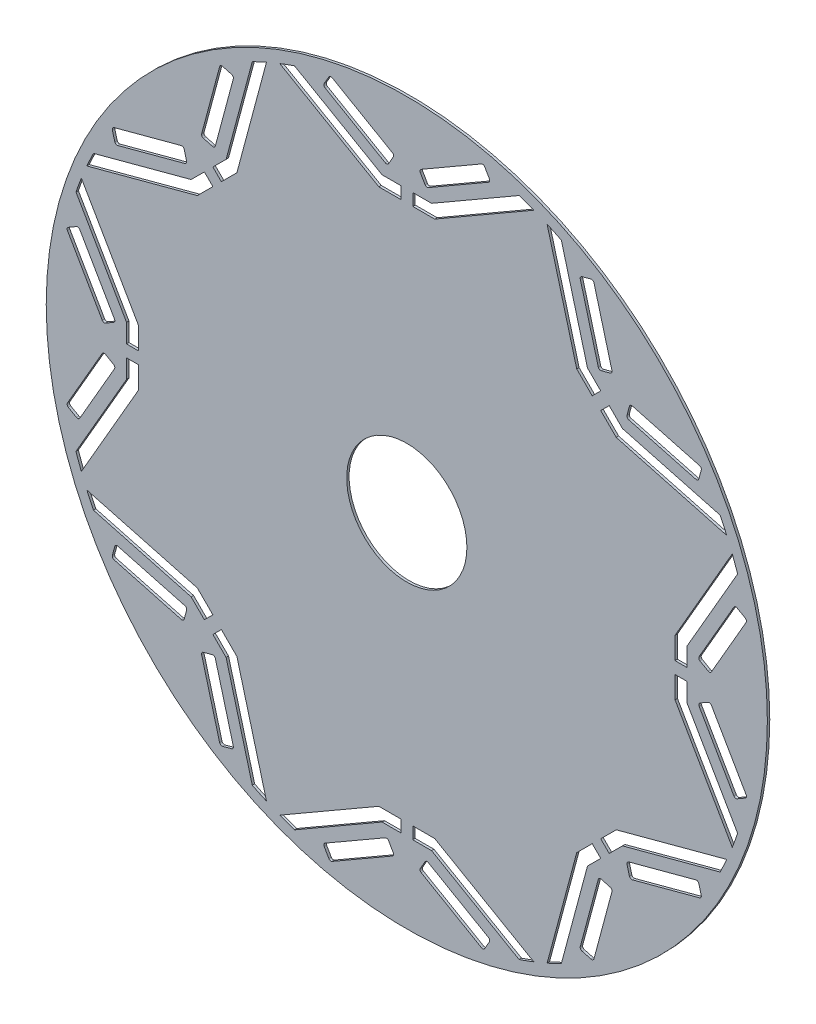
SolidWorks part; units mm, degrees
material "M19 Silicon Steel (29 Gauge)"
ref_plane "Front Plane" through (0, 0, 0) normal (0, 0, 1) x (1, 0, 0)
ref_plane "Top Plane" through (0, 0, 0) normal (0, 1, 0) x (1, 0, 0)
ref_plane "Right Plane" through (0, 0, 0) normal (1, 0, 0) x (0, 0, -1)
sketch "Rotor sketch" plane through (0, 0, 0) normal (0, 0, 1) x (1, 0, 0)
  line L0 (0, 0) -> (0, 45) construction
  line L1 (2.6839, 36.4771) -> (10.2011, 40.8171)
  line L2 (2.2741, 36.5869) -> (1.6891, 37.6002)
  line L3 (10.3109, 41.2269) -> (9.7259, 42.2402)
  line L4 (1.7989, 38.01) -> (9.3161, 42.35)
  line L5 (2.4241, 36.3271) -> (9.5759, 42.5) construction
  line L6 (10.4609, 40.9671) -> (1.5391, 37.86) construction
  line L7 (-10.4609, 40.9671) -> (-1.5391, 37.86) construction
  line L8 (-2.4241, 36.3271) -> (-9.5759, 42.5) construction
  line L9 (-1.7989, 38.01) -> (-9.3161, 42.35)
  line L10 (-10.3109, 41.2269) -> (-9.7259, 42.2402)
  line L11 (-2.2741, 36.5869) -> (-1.6891, 37.6002)
  line L12 (-2.6839, 36.4771) -> (-10.2011, 40.8171)
  line L13 (25.6051, 28.1492) -> (23.3585, 36.5334)
  line L14 (24.2628, 27.4789) -> (25.3929, 27.7818)
  line L15 (23.8954, 27.6911) -> (21.6488, 36.0753)
  line L16 (21.861, 36.4427) -> (22.9911, 36.7455)
  line L17 (27.4789, 24.2628) -> (27.7818, 25.3929)
  line L18 (28.1492, 25.6051) -> (36.5334, 23.3585)
  line L19 (36.4427, 21.861) -> (36.7455, 22.9911)
  line L20 (27.6911, 23.8954) -> (36.0753, 21.6488)
  line L21 (38.01, 1.7989) -> (42.35, 9.3161)
  line L22 (36.5869, 2.2741) -> (37.6002, 1.6891)
  line L23 (36.4771, 2.6839) -> (40.8171, 10.2011)
  line L24 (41.2269, 10.3109) -> (42.2402, 9.7259)
  line L25 (36.5869, -2.2741) -> (37.6002, -1.6891)
  line L26 (38.01, -1.7989) -> (42.35, -9.3161)
  line L27 (41.2269, -10.3109) -> (42.2402, -9.7259)
  line L28 (36.4771, -2.6839) -> (40.8171, -10.2011)
  line L29 (28.1492, -25.6051) -> (36.5334, -23.3585)
  line L30 (27.4789, -24.2628) -> (27.7818, -25.3929)
  line L31 (27.6911, -23.8954) -> (36.0753, -21.6488)
  line L32 (36.4427, -21.861) -> (36.7455, -22.9911)
  line L33 (24.2628, -27.4789) -> (25.3929, -27.7818)
  line L34 (25.6051, -28.1492) -> (23.3585, -36.5334)
  line L35 (21.861, -36.4427) -> (22.9911, -36.7455)
  line L36 (23.8954, -27.6911) -> (21.6488, -36.0753)
  line L37 (1.7989, -38.01) -> (9.3161, -42.35)
  line L38 (2.2741, -36.5869) -> (1.6891, -37.6002)
  line L39 (2.6839, -36.4771) -> (10.2011, -40.8171)
  line L40 (10.3109, -41.2269) -> (9.7259, -42.2402)
  line L41 (-2.2741, -36.5869) -> (-1.6891, -37.6002)
  line L42 (-1.7989, -38.01) -> (-9.3161, -42.35)
  line L43 (-10.3109, -41.2269) -> (-9.7259, -42.2402)
  line L44 (-2.6839, -36.4771) -> (-10.2011, -40.8171)
  line L45 (-25.6051, -28.1492) -> (-23.3585, -36.5334)
  line L46 (-24.2628, -27.4789) -> (-25.3929, -27.7818)
  line L47 (-23.8954, -27.6911) -> (-21.6488, -36.0753)
  line L48 (-21.861, -36.4427) -> (-22.9911, -36.7455)
  line L49 (-27.4789, -24.2628) -> (-27.7818, -25.3929)
  line L50 (-28.1492, -25.6051) -> (-36.5334, -23.3585)
  line L51 (-36.4427, -21.861) -> (-36.7455, -22.9911)
  line L52 (-27.6911, -23.8954) -> (-36.0753, -21.6488)
  line L53 (-38.01, -1.7989) -> (-42.35, -9.3161)
  line L54 (-36.5869, -2.2741) -> (-37.6002, -1.6891)
  line L55 (-36.4771, -2.6839) -> (-40.8171, -10.2011)
  line L56 (-41.2269, -10.3109) -> (-42.2402, -9.7259)
  line L57 (-36.5869, 2.2741) -> (-37.6002, 1.6891)
  line L58 (-38.01, 1.7989) -> (-42.35, 9.3161)
  line L59 (-41.2269, 10.3109) -> (-42.2402, 9.7259)
  line L60 (-36.4771, 2.6839) -> (-40.8171, 10.2011)
  line L61 (-28.1492, 25.6051) -> (-36.5334, 23.3585)
  line L62 (-27.4789, 24.2628) -> (-27.7818, 25.3929)
  line L63 (-27.6911, 23.8954) -> (-36.0753, 21.6488)
  line L64 (-36.4427, 21.861) -> (-36.7455, 22.9911)
  line L65 (-24.2628, 27.4789) -> (-25.3929, 27.7818)
  line L66 (-25.6051, 28.1492) -> (-23.3585, 36.5334)
  line L67 (-21.861, 36.4427) -> (-22.9911, 36.7455)
  line L68 (-23.8954, 27.6911) -> (-21.6488, 36.0753)
  line L69 (0, 0) -> (-9.8912, 43.8995) construction
  circle A0 centre (0, 0) radius 45
  circle A1 centre (0, 0) radius 7.5
  arc A2 (-21.861, 36.4427) -> (-21.6488, 36.0753) centre (-21.9386, 36.153) cw
  arc A3 (-23.3585, 36.5334) -> (-22.9911, 36.7455) centre (-23.0688, 36.4558) cw
  arc A4 (-24.2628, 27.4789) -> (-23.8954, 27.6911) centre (-24.1852, 27.7687) ccw
  arc A5 (-25.3929, 27.7818) -> (-25.6051, 28.1492) centre (-25.3153, 28.0715) cw
  arc A6 (-27.4789, 24.2628) -> (-27.6911, 23.8954) centre (-27.7687, 24.1852) cw
  arc A7 (-28.1492, 25.6051) -> (-27.7818, 25.3929) centre (-28.0715, 25.3153) cw
  arc A8 (-36.5334, 23.3585) -> (-36.7455, 22.9911) centre (-36.4558, 23.0688) ccw
  arc A9 (-36.0753, 21.6488) -> (-36.4427, 21.861) centre (-36.153, 21.9386) cw
  arc A10 (-36.5869, 2.2741) -> (-36.4771, 2.6839) centre (-36.7369, 2.5339) ccw
  arc A11 (-37.6002, 1.6891) -> (-38.01, 1.7989) centre (-37.7502, 1.9489) cw
  arc A12 (-41.2269, 10.3109) -> (-40.8171, 10.2011) centre (-41.0769, 10.0511) cw
  arc A13 (-42.35, 9.3161) -> (-42.2402, 9.7259) centre (-42.0902, 9.4661) cw
  arc A14 (-36.5869, -2.2741) -> (-36.4771, -2.6839) centre (-36.7369, -2.5339) cw
  arc A15 (-38.01, -1.7989) -> (-37.6002, -1.6891) centre (-37.7502, -1.9489) cw
  arc A16 (-42.35, -9.3161) -> (-42.2402, -9.7259) centre (-42.0902, -9.4661) ccw
  arc A17 (-40.8171, -10.2011) -> (-41.2269, -10.3109) centre (-41.0769, -10.0511) cw
  arc A18 (-36.5334, -23.3585) -> (-36.7455, -22.9911) centre (-36.4558, -23.0688) cw
  arc A19 (-36.4427, -21.861) -> (-36.0753, -21.6488) centre (-36.153, -21.9386) cw
  arc A20 (-27.4789, -24.2628) -> (-27.6911, -23.8954) centre (-27.7687, -24.1852) ccw
  arc A21 (-27.7818, -25.3929) -> (-28.1492, -25.6051) centre (-28.0715, -25.3153) cw
  arc A22 (-24.2628, -27.4789) -> (-23.8954, -27.6911) centre (-24.1852, -27.7687) cw
  arc A23 (-25.6051, -28.1492) -> (-25.3929, -27.7818) centre (-25.3153, -28.0715) cw
  arc A24 (-23.3585, -36.5334) -> (-22.9911, -36.7455) centre (-23.0688, -36.4558) ccw
  arc A25 (-21.6488, -36.0753) -> (-21.861, -36.4427) centre (-21.9386, -36.153) cw
  arc A26 (-10.3109, -41.2269) -> (-10.2011, -40.8171) centre (-10.0511, -41.0769) cw
  arc A27 (-9.3161, -42.35) -> (-9.7259, -42.2402) centre (-9.4661, -42.0902) cw
  arc A28 (-1.6891, -37.6002) -> (-1.7989, -38.01) centre (-1.9489, -37.7502) cw
  arc A29 (-2.2741, -36.5869) -> (-2.6839, -36.4771) centre (-2.5339, -36.7369) ccw
  arc A30 (10.2011, -40.8171) -> (10.3109, -41.2269) centre (10.0511, -41.0769) cw
  arc A31 (9.3161, -42.35) -> (9.7259, -42.2402) centre (9.4661, -42.0902) ccw
  arc A32 (1.7989, -38.01) -> (1.6891, -37.6002) centre (1.9489, -37.7502) cw
  arc A33 (2.2741, -36.5869) -> (2.6839, -36.4771) centre (2.5339, -36.7369) cw
  arc A34 (23.3585, -36.5334) -> (22.9911, -36.7455) centre (23.0688, -36.4558) cw
  arc A35 (21.861, -36.4427) -> (21.6488, -36.0753) centre (21.9386, -36.153) cw
  arc A36 (24.2628, -27.4789) -> (23.8954, -27.6911) centre (24.1852, -27.7687) ccw
  arc A37 (25.3929, -27.7818) -> (25.6051, -28.1492) centre (25.3153, -28.0715) cw
  arc A38 (28.1492, -25.6051) -> (27.7818, -25.3929) centre (28.0715, -25.3153) cw
  arc A39 (27.4789, -24.2628) -> (27.6911, -23.8954) centre (27.7687, -24.1852) cw
  arc A40 (36.5334, -23.3585) -> (36.7455, -22.9911) centre (36.4558, -23.0688) ccw
  arc A41 (36.0753, -21.6488) -> (36.4427, -21.861) centre (36.153, -21.9386) cw
  arc A42 (41.2269, -10.3109) -> (40.8171, -10.2011) centre (41.0769, -10.0511) cw
  arc A43 (42.35, -9.3161) -> (42.2402, -9.7259) centre (42.0902, -9.4661) cw
  arc A44 (37.6002, -1.6891) -> (38.01, -1.7989) centre (37.7502, -1.9489) cw
  arc A45 (36.5869, -2.2741) -> (36.4771, -2.6839) centre (36.7369, -2.5339) ccw
  arc A46 (38.01, 1.7989) -> (37.6002, 1.6891) centre (37.7502, 1.9489) cw
  arc A47 (36.5869, 2.2741) -> (36.4771, 2.6839) centre (36.7369, 2.5339) cw
  arc A48 (40.8171, 10.2011) -> (41.2269, 10.3109) centre (41.0769, 10.0511) cw
  arc A49 (42.35, 9.3161) -> (42.2402, 9.7259) centre (42.0902, 9.4661) ccw
  arc A50 (36.4427, 21.861) -> (36.0753, 21.6488) centre (36.153, 21.9386) cw
  arc A51 (36.5334, 23.3585) -> (36.7455, 22.9911) centre (36.4558, 23.0688) cw
  arc A52 (27.4789, 24.2628) -> (27.6911, 23.8954) centre (27.7687, 24.1852) ccw
  arc A53 (27.7818, 25.3929) -> (28.1492, 25.6051) centre (28.0715, 25.3153) cw
  arc A54 (24.2628, 27.4789) -> (23.8954, 27.6911) centre (24.1852, 27.7687) cw
  arc A55 (25.6051, 28.1492) -> (25.3929, 27.7818) centre (25.3153, 28.0715) cw
  arc A56 (23.3585, 36.5334) -> (22.9911, 36.7455) centre (23.0688, 36.4558) ccw
  arc A57 (21.6488, 36.0753) -> (21.861, 36.4427) centre (21.9386, 36.153) cw
  arc A58 (10.2011, 40.8171) -> (10.3109, 41.2269) centre (10.0511, 41.0769) ccw
  arc A59 (9.7259, 42.2402) -> (9.3161, 42.35) centre (9.4661, 42.0902) ccw
  arc A60 (1.6891, 37.6002) -> (1.7989, 38.01) centre (1.9489, 37.7502) cw
  arc A61 (2.2741, 36.5869) -> (2.6839, 36.4771) centre (2.5339, 36.7369) ccw
  arc A62 (-10.2011, 40.8171) -> (-10.3109, 41.2269) centre (-10.0511, 41.0769) cw
  arc A63 (-2.6839, 36.4771) -> (-2.2741, 36.5869) centre (-2.5339, 36.7369) ccw
  arc A64 (-1.6891, 37.6002) -> (-1.7989, 38.01) centre (-1.9489, 37.7502) ccw
  arc A65 (-9.7259, 42.2402) -> (-9.3161, 42.35) centre (-9.4661, 42.0902) cw
  point P6 (6, 39.4136)
  point P16 (-6, 39.4136)
  point P74 (0, 0)
  dimension "D6" = 90
  dimension "D7" = 15
  dimension "D10" = 0.3
  dimension "D1" = 9.28
  dimension "D2" = 1.77
  dimension "D3" = 60
  dimension "D4" = 6
  dimension "D5" = 2.5
  dimension "D9" = 1.4346
  dimension "D8" = 8
extrude "Boss-Extrude1" add sketch "Rotor sketch" along normal mid plane 0.3
sketch "Saliency grooves" plane through (0, 0, 0.15) normal (0, 0, 1) x (1, 0, 0)
  line L0 (-12.8371, 38.875) -> (-3.4878, 33.4771)
  line L3 (-14.0139, 41.2864) -> (-3.0859, 34.9771)
  line L4 (0.75, 34.9771) -> (3.0859, 34.9771)
  line L5 (-3.4878, 33.4771) -> (-14.0139, 41.2864) construction
  line L6 (0, 0) -> (0, 45) construction
  line L7 (3.4878, 33.4771) -> (14.0139, 41.2864) construction
  line L8 (-0.75, 33.4771) -> (-3.4878, 33.4771)
  line L9 (14.0139, 41.2864) -> (3.0859, 34.9771)
  line L12 (12.8371, 38.875) -> (3.4878, 33.4771)
  line L13 (-3.0859, 34.9771) -> (-0.75, 34.9771)
  line L14 (3.4878, 33.4771) -> (0.75, 33.4771)
  line L15 (0, 43.6) -> (0, 45) construction
  line L16 (-10.2011, 40.8171) -> (-2.6839, 36.4771) construction
  line L17 (-10.2011, 40.8171) -> (-2.6839, 36.4771) construction
  line L18 (-0.75, 33.4771) -> (0.75, 34.9771) construction
  line L20 (-0.75, 33.4771) -> (-0.75, 34.9771)
  line L22 (0.75, 33.4771) -> (0.75, 34.9771)
  line L23 (-12.8371, 38.875) -> (-15.8526, 40.616)
  line L24 (12.8371, 38.875) -> (15.8526, 40.616)
  line L25 (19.2846, 39.1033) -> (22.5505, 26.9146)
  line L26 (18.4115, 36.566) -> (21.2057, 26.1382)
  line L27 (18.4115, 36.566) -> (17.5103, 39.9293)
  line L28 (23.1416, 24.2022) -> (21.2057, 26.1382)
  line L29 (22.5505, 26.9146) -> (24.2022, 25.2629)
  line L30 (23.1416, 24.2022) -> (24.2022, 25.2629)
  line L31 (25.2629, 24.2022) -> (26.9146, 22.5505)
  line L32 (24.2022, 23.1416) -> (25.2629, 24.2022)
  line L33 (26.1382, 21.2057) -> (24.2022, 23.1416)
  line L34 (36.566, 18.4115) -> (26.1382, 21.2057)
  line L35 (39.1033, 19.2846) -> (26.9146, 22.5505)
  line L36 (36.566, 18.4115) -> (39.9293, 17.5103)
  line L37 (41.2864, 14.0139) -> (34.9771, 3.0859)
  line L38 (38.875, 12.8371) -> (33.4771, 3.4878)
  line L39 (38.875, 12.8371) -> (40.616, 15.8526)
  line L40 (33.4771, 0.75) -> (33.4771, 3.4878)
  line L41 (34.9771, 3.0859) -> (34.9771, 0.75)
  line L42 (33.4771, 0.75) -> (34.9771, 0.75)
  line L43 (34.9771, -0.75) -> (34.9771, -3.0859)
  line L44 (33.4771, -0.75) -> (34.9771, -0.75)
  line L45 (33.4771, -3.4878) -> (33.4771, -0.75)
  line L46 (38.875, -12.8371) -> (33.4771, -3.4878)
  line L47 (41.2864, -14.0139) -> (34.9771, -3.0859)
  line L48 (38.875, -12.8371) -> (40.616, -15.8526)
  line L49 (39.1033, -19.2846) -> (26.9146, -22.5505)
  line L50 (36.566, -18.4115) -> (26.1382, -21.2057)
  line L51 (36.566, -18.4115) -> (39.9293, -17.5103)
  line L52 (24.2022, -23.1416) -> (26.1382, -21.2057)
  line L53 (26.9146, -22.5505) -> (25.2629, -24.2022)
  line L54 (24.2022, -23.1416) -> (25.2629, -24.2022)
  line L55 (24.2022, -25.2629) -> (22.5505, -26.9146)
  line L56 (23.1416, -24.2022) -> (24.2022, -25.2629)
  line L57 (21.2057, -26.1382) -> (23.1416, -24.2022)
  line L58 (18.4115, -36.566) -> (21.2057, -26.1382)
  line L59 (19.2846, -39.1033) -> (22.5505, -26.9146)
  line L60 (18.4115, -36.566) -> (17.5103, -39.9293)
  line L61 (14.0139, -41.2864) -> (3.0859, -34.9771)
  line L62 (12.8371, -38.875) -> (3.4878, -33.4771)
  line L63 (12.8371, -38.875) -> (15.8526, -40.616)
  line L64 (0.75, -33.4771) -> (3.4878, -33.4771)
  line L65 (3.0859, -34.9771) -> (0.75, -34.9771)
  line L66 (0.75, -33.4771) -> (0.75, -34.9771)
  line L67 (-0.75, -34.9771) -> (-3.0859, -34.9771)
  line L68 (-0.75, -33.4771) -> (-0.75, -34.9771)
  line L69 (-3.4878, -33.4771) -> (-0.75, -33.4771)
  line L70 (-12.8371, -38.875) -> (-3.4878, -33.4771)
  line L71 (-14.0139, -41.2864) -> (-3.0859, -34.9771)
  line L72 (-12.8371, -38.875) -> (-15.8526, -40.616)
  line L73 (-19.2846, -39.1033) -> (-22.5505, -26.9146)
  line L74 (-18.4115, -36.566) -> (-21.2057, -26.1382)
  line L75 (-18.4115, -36.566) -> (-17.5103, -39.9293)
  line L76 (-23.1416, -24.2022) -> (-21.2057, -26.1382)
  line L77 (-22.5505, -26.9146) -> (-24.2022, -25.2629)
  line L78 (-23.1416, -24.2022) -> (-24.2022, -25.2629)
  line L79 (-25.2629, -24.2022) -> (-26.9146, -22.5505)
  line L80 (-24.2022, -23.1416) -> (-25.2629, -24.2022)
  line L81 (-26.1382, -21.2057) -> (-24.2022, -23.1416)
  line L82 (-36.566, -18.4115) -> (-26.1382, -21.2057)
  line L83 (-39.1033, -19.2846) -> (-26.9146, -22.5505)
  line L84 (-36.566, -18.4115) -> (-39.9293, -17.5103)
  line L85 (-41.2864, -14.0139) -> (-34.9771, -3.0859)
  line L86 (-38.875, -12.8371) -> (-33.4771, -3.4878)
  line L87 (-38.875, -12.8371) -> (-40.616, -15.8526)
  line L88 (-33.4771, -0.75) -> (-33.4771, -3.4878)
  line L89 (-34.9771, -3.0859) -> (-34.9771, -0.75)
  line L90 (-33.4771, -0.75) -> (-34.9771, -0.75)
  line L91 (-34.9771, 0.75) -> (-34.9771, 3.0859)
  line L92 (-33.4771, 0.75) -> (-34.9771, 0.75)
  line L93 (-33.4771, 3.4878) -> (-33.4771, 0.75)
  line L94 (-38.875, 12.8371) -> (-33.4771, 3.4878)
  line L95 (-41.2864, 14.0139) -> (-34.9771, 3.0859)
  line L96 (-38.875, 12.8371) -> (-40.616, 15.8526)
  line L97 (-39.1033, 19.2846) -> (-26.9146, 22.5505)
  line L98 (-36.566, 18.4115) -> (-26.1382, 21.2057)
  line L99 (-36.566, 18.4115) -> (-39.9293, 17.5103)
  line L100 (-24.2022, 23.1416) -> (-26.1382, 21.2057)
  line L101 (-26.9146, 22.5505) -> (-25.2629, 24.2022)
  line L102 (-24.2022, 23.1416) -> (-25.2629, 24.2022)
  line L103 (-24.2022, 25.2629) -> (-22.5505, 26.9146)
  line L104 (-23.1416, 24.2022) -> (-24.2022, 25.2629)
  line L105 (-21.2057, 26.1382) -> (-23.1416, 24.2022)
  line L106 (-18.4115, 36.566) -> (-21.2057, 26.1382)
  line L107 (-19.2846, 39.1033) -> (-22.5505, 26.9146)
  line L108 (-18.4115, 36.566) -> (-17.5103, 39.9293)
  circle A0 centre (0, 0) radius 45 construction
  circle A1 centre (0, 0) radius 43.6
  point P1 (-9.1257, 37.6599)
  point P15 (9.1257, 37.6599)
  point P24 (0, 34.2271)
  point P128 (0, 0)
  dimension "D1" = 1.4
  dimension "D2" = 1.5
  dimension "D3" = 1.5
  dimension "D4" = 1.5
  dimension "D5" = 1.5
  dimension "D6" = 1.5
  dimension "D7" = 8
extrude "Cut-Extrude1" cut sketch "Saliency grooves" against normal through all contours L97 A1 L99 L98 L100 L102 L101 | L108 A1 L107 L103 L104 L105 L106 | L24 A1 L9 L4 L22 L14 L12 | L3 A1 L23 L0 L8 L20 L13 | L25 A1 L27 L26 L28 L30 L29 | L36 A1 L35 L31 L32 L33 L34 | L37 A1 L39 L38 L40 L42 L41 | L48 A1 L47 L43 L44 L45 L46 | L96 A1 L95 L91 L92 L93 L94 | L85 A1 L87 L86 L88 L90 L89 | L84 A1 L83 L79 L80 L81 L82 | L73 A1 L75 L74 L76 L78 L77 | L72 A1 L71 L67 L68 L69 L70 | L61 A1 L63 L62 L64 L66 L65 | L60 A1 L59 L55 L56 L57 L58 | L49 A1 L51 L50 L52 L54 L53
equation "\"Magnet thickness\"= 1.57mm"
equation "\"Magnet short side\"= 9.08mm"
equation "\"Magnet long side\"= 19.14mm"
equation "\"D2@Rotor sketch\"=\"Magnet thickness\" + 0.2"
equation "\"Magnet angle\"= 60deg"
equation "\"Magnet distance from center\"= 6mm"
equation "\"Magnet distance from top\"= 2.5mm"
equation "\"D1@Rotor sketch\"=\"Magnet short side\" +0.2"
equation "\"D4@Rotor sketch\"=\"Magnet distance from center\""
equation "\"D3@Rotor sketch\"=\"Magnet angle\""
equation "\"Rotor outer Φ\"= 90mm"
equation "\"Rotor inner Φ\"= 15mm"
equation "\"D7@Rotor sketch\"=\"Rotor inner Φ\""
equation "\"D6@Rotor sketch\"=\"Rotor outer Φ\""
equation "\"Lamination thickness\"= 0.3mm"
equation "\"D1@Boss-Extrude1\"=\"Lamination thickness\""
equation "\"D5@Rotor sketch\"=\"Magnet distance from top\""
equation "\"Magnet hole fillet\"= 0.3mm"
equation "\"D10@Rotor sketch\"=\"Magnet hole fillet\""
equation "\"V pair count\"= 8"
equation "\"D8@Rotor sketch\"=\"V pair count\""
equation "\"Bridge thickness\"= 1.4mm"
equation "\"Groove thickness\"= 1.5mm"
equation "\"Center bridge width\"= 1.5mm"
equation "\"Groove-magnet clearance\"= 1.5mm"
equation "\"D1@Saliency grooves\"=\"Bridge thickness\""
equation "\"D2@Saliency grooves\"=\"Groove thickness\""
equation "\"D3@Saliency grooves\"=\"Center bridge width\""
equation "\"D4@Saliency grooves\"=\"Groove-magnet clearance\""
equation "\"D5@Saliency grooves\"=\"Groove-magnet clearance\""
equation "\"D6@Saliency grooves\"=\"Groove thickness\""
